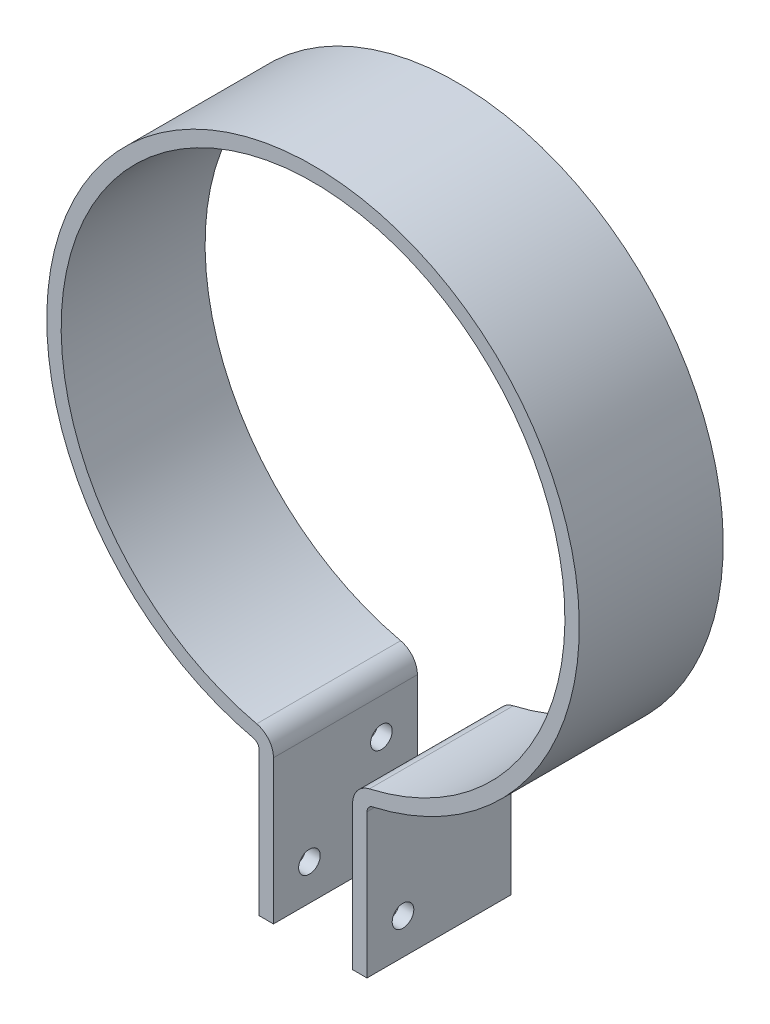
SolidWorks part; units mm, degrees
ref_plane "Plan de face" through (0, 0, 0) normal (0, 0, 1) x (1, 0, 0)
ref_plane "Plan de dessus" through (0, 0, 0) normal (0, 1, 0) x (1, 0, 0)
ref_plane "Plan de droite" through (0, 0, 0) normal (1, 0, 0) x (0, 0, -1)
sketch "Esquisse7" plane through (0, 0, 0) normal (0, 0, 1) x (1, 0, 0)
  line L0 (5.5, -57.0371) -> (7.5, -57.0371)
  line L1 (-7.5, -57.0371) -> (-5.5, -57.0371)
  line L2 (-7.5, -57.0371) -> (-7.5, -37.0371)
  line L3 (5.5, -51.1606) -> (7.5, -57.0371) construction
  line L4 (7.5, -57.0371) -> (7.5, -37.0371)
  line L5 (-7.5, -57.0371) -> (-5.5, -51.1606) construction
  line L8 (-5.5, -57.0371) -> (-5.5, -37.0371)
  line L10 (5.5, -57.0371) -> (5.5, -37.0371)
  arc A0 (7.8289, -34.1132) -> (-7.8289, -34.1132) centre (0, 0) ccw
  arc A1 (8.2763, -36.0625) -> (-8.2763, -36.0625) centre (0, 0) ccw
  arc A2 (-7.5, -37.0371) -> (-8.2763, -36.0625) centre (-8.5, -37.0371) ccw
  arc A4 (8.2763, -36.0625) -> (7.5, -37.0371) centre (8.5, -37.0371) ccw
  arc A5 (7.8289, -34.1132) -> (5.5, -37.0371) centre (8.5, -37.0371) ccw
  arc A6 (-5.5, -37.0371) -> (-7.8289, -34.1132) centre (-8.5, -37.0371) ccw
  point P4 (0, -35)
  point P5 (-9.9543, -32.6233)
  point P9 (0, -35)
  point P18 (-7.8289, -34.1132)
  point P19 (-5.5, -37.0371)
  point P24 (5.5, -37.0371)
  point P25 (-7.5, -37.0371)
  dimension "D1" = 70
  dimension "D5" = 2
  dimension "D6" = 2
  dimension "D7" = 20
extrude "Extrusion2" add sketch "Esquisse7" along normal blind 20
sketch "Esquisse8" plane through (-7.5, 0, 0) normal (-1, 0, 0) x (0, 0, 1)
  line L0 (20, -37.0371) -> (20, -57.0371) construction
  line L1 (20, -57.0371) -> (0, -57.0371) construction
  circle A0 centre (15, -52.0371) radius 1.5
  dimension "D1" = 3
  dimension "D2" = 5
  dimension "D3" = 5
extrude "Extrusion3" cut sketch "Esquisse8" against normal through all
sketch "Esquisse9" plane through (-7.5, 0, 0) normal (-1, 0, 0) x (0, 0, 1)
  line L0 (0, -37.0371) -> (0, -57.0371) construction
  line L1 (20, -57.0371) -> (0, -57.0371) construction
  circle A0 centre (5, -42.0371) radius 1.5
  dimension "D1" = 3
  dimension "D2" = 5
  dimension "D3" = 15
extrude "Extrusion4" cut sketch "Esquisse9" against normal through all
